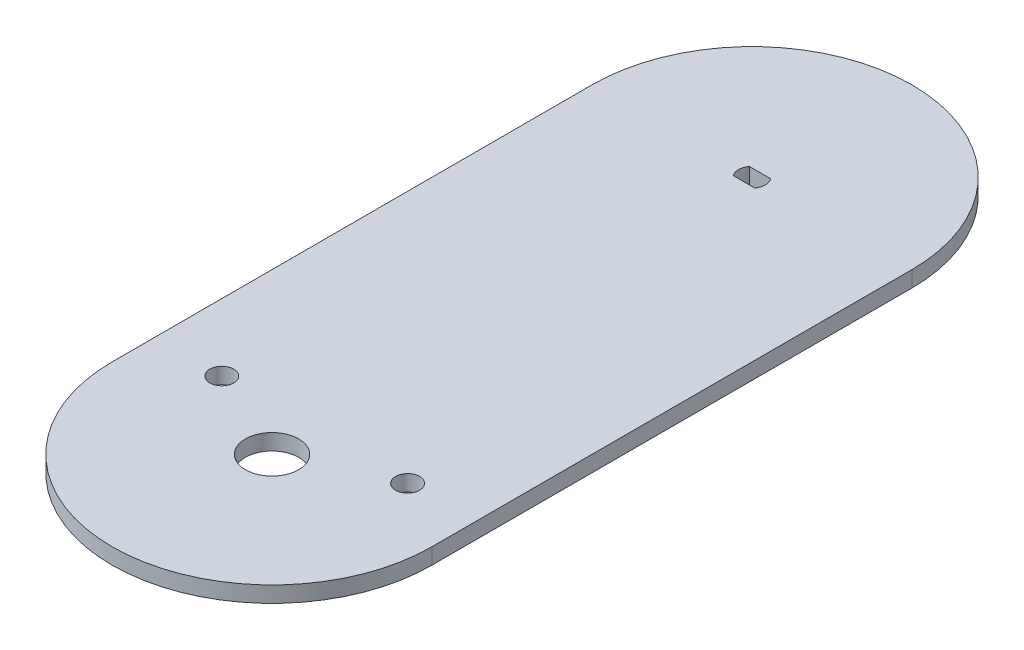
SolidWorks part; units mm, degrees
ref_plane "Front Plane" through (0, 0, 0) normal (0, 0, 1) x (1, 0, 0)
ref_plane "Top Plane" through (0, 0, 0) normal (0, 1, 0) x (1, 0, 0)
ref_plane "Right Plane" through (0, 0, 0) normal (1, 0, 0) x (0, 0, -1)
sketch "Sketch1" plane through (0, 0, 0) normal (0, 1, 0) x (1, 0, 0)
  line L0 (-30, 0) -> (-30, -90)
  line L1 (30, 0) -> (30, -90)
  line L2 (-2, -1.5) -> (2, -1.5)
  line L5 (-2, 1.5) -> (2, 1.5)
  line L6 (-17.425, -82) -> (17.425, -82) construction
  arc A0 (30, 0) -> (-30, 0) centre (0, 0) ccw
  arc A1 (-30, -90) -> (30, -90) centre (0, -90) ccw
  circle A2 centre (0, -90) radius 5
  arc A3 (-2, 1.5) -> (-2, -1.5) centre (0, 0) ccw
  arc A4 (2, -1.5) -> (2, 1.5) centre (0, 0) ccw
  circle A5 centre (-17.425, -82) radius 2.25
  circle A6 centre (17.425, -82) radius 2.25
  point P14 (0, -90)
  point P17 (0, -82)
  dimension "D1" = 60
  dimension "D3" = 10
  dimension "D4" = 34.85
  dimension "D5" = 5
  dimension "D6" = 8
  dimension "D2" = 90
extrude "Boss-Extrude1" add sketch "Sketch1" along normal blind 3
